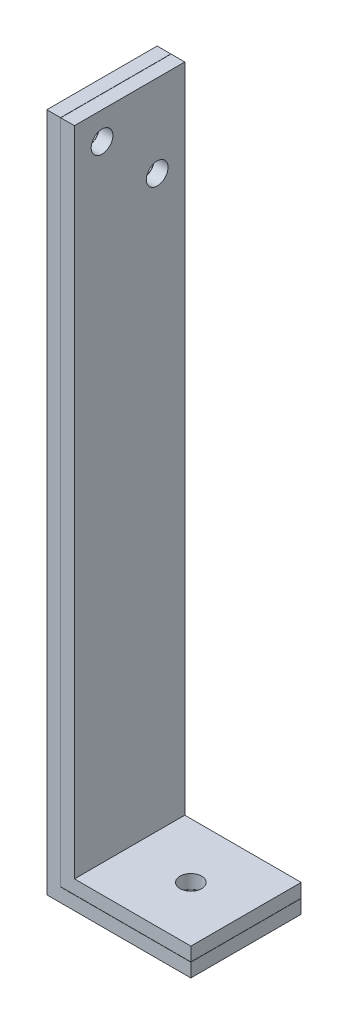
SolidWorks part; units mm, degrees
ref_plane "Alzado" through (0, 0, 0) normal (0, 0, 1) x (1, 0, 0)
ref_plane "Planta" through (0, 0, 0) normal (0, 1, 0) x (1, 0, 0)
ref_plane "Vista lateral" through (0, 0, 0) normal (1, 0, 0) x (0, 0, -1)
sketch "Croquis1" plane through (0, 0, 0) normal (0, 0, 1) x (1, 0, 0)
  line L0 (0, 0) -> (66.31, 0)
  line L1 (0, 0) -> (0, 313.04)
  line L2 (6.31, 6.31) -> (66.31, 6.31)
  line L3 (6.31, 6.31) -> (6.31, 313.04)
  line L4 (66.31, 6.31) -> (66.31, 0)
  line L5 (6.31, 313.04) -> (0, 313.04)
  dimension "D1" = 66.31
  dimension "D2" = 313.04
  dimension "D3" = 6.31
extrude "Saliente-Extruir1" add sketch "Croquis1" along normal blind 50.8
sketch "Croquis2" plane through (0, 0, 50.8) normal (0, 0, 1) x (1, 0, 0)
  line L0 (6.41, 313.04) -> (12.72, 313.04)
  line L1 (12.72, 313.04) -> (12.72, 12.72)
  line L2 (12.72, 12.72) -> (66.31, 12.72)
  line L3 (66.31, 12.72) -> (66.31, 6.41)
  line L4 (66.31, 6.41) -> (6.41, 6.41)
  line L5 (6.41, 6.41) -> (6.41, 313.04)
  line L6 (6.31, 6.31) -> (6.31, 313.04) construction
  line L7 (66.31, 6.31) -> (6.31, 6.31) construction
  line L9 (66.31, 6.31) -> (66.31, 6.9586) construction
  line L10 (6.31, 313.04) -> (0, 313.04) construction
  line L11 (3.155, 313.04) -> (16.3816, 313.04) construction
  dimension "D1" = 0.1
  dimension "D2" = 0.1
  dimension "D3" = 6.31
  dimension "D4" = 6.31
extrude "Saliente-Extruir2" add sketch "Croquis2" against normal blind 50.8 separate body
sketch "Croquis3" plane through (0, 0, 0) normal (-1, 0, 0) x (0, 0, 1)
  line L0 (0, 313.04) -> (50.8, 313.04) construction
  line L1 (50.8, 313.04) -> (50.8, 262.24) construction
  line L2 (50.8, 313.04) -> (50.8, 0) construction
  line L3 (50.8, 262.24) -> (0, 262.24) construction
  line L4 (0, 313.04) -> (0, 0) construction
  line L5 (0, 262.24) -> (0, 313.04) construction
  line L6 (0, 262.24) -> (50.8, 313.04) construction
  line L7 (50.8, 313.04) -> (25.4, 287.64) construction
  line L8 (25.4, 287.64) -> (38.1, 300.34) construction
  line L9 (38.1, 300.34) -> (45.8211, 300.34) construction
  line L10 (25.4, 287.64) -> (0, 262.24) construction
  line L11 (0, 262.24) -> (12.7, 274.94) construction
  circle A0 centre (12.7, 274.94) radius 5
  circle A1 centre (38.1, 300.34) radius 5
  dimension "D2" = 10
  dimension "D3" = 10
  dimension "D1" = 50.8
extrude "Cortar-Extruir1" cut sketch "Croquis3" against normal blind 102.525
sketch "Croquis5" plane through (0, 12.72, 0) normal (0, 1, 0) x (1, 0, 0)
  line L0 (36.243, -23.6058) -> (40.91, -25.4) construction
  line L1 (40.91, -25.4) -> (45.91, -25.4) construction
  circle A0 centre (40.91, -25.4) radius 5 construction
  circle A1 centre (40.91, -25.4) radius 5
extrude "Cortar-Extruir2" cut sketch "Croquis5" against normal blind 24.525
